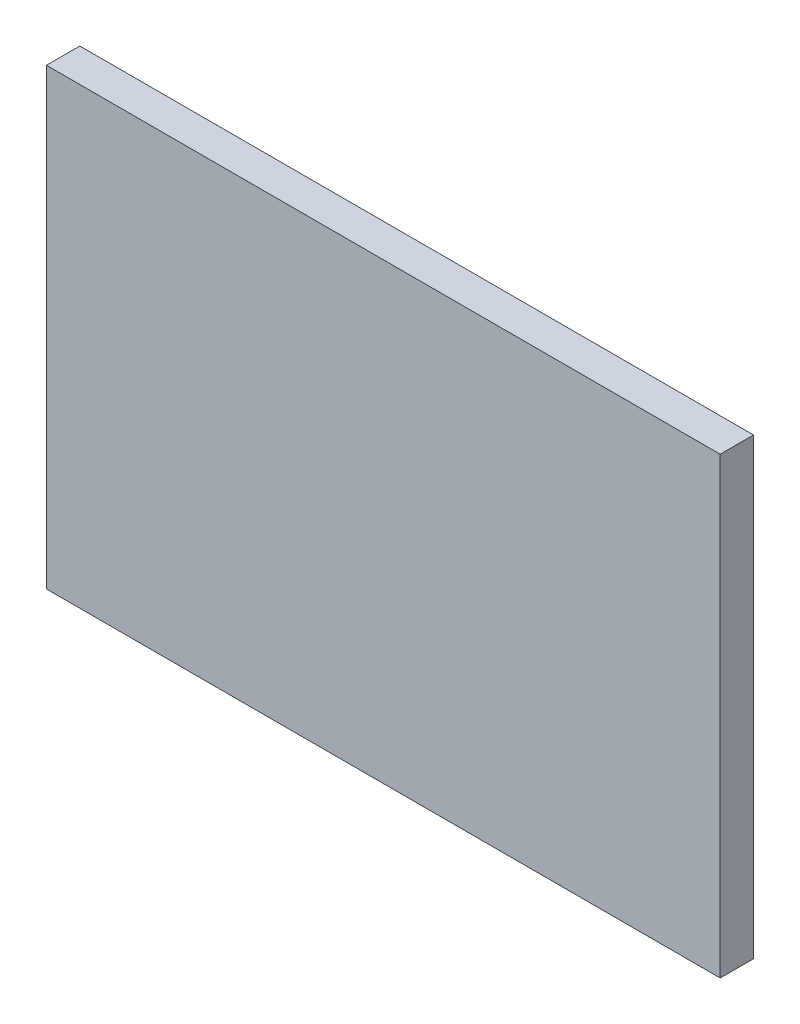
SolidWorks part; units mm, degrees
ref_plane "前视基准面" through (0, 0, 0) normal (0, 0, 1) x (1, 0, 0)
ref_plane "上视基准面" through (0, 0, 0) normal (0, 1, 0) x (1, 0, 0)
ref_plane "右视基准面" through (0, 0, 0) normal (1, 0, 0) x (0, 0, -1)
other "Configuration Table"
sketch "草图1" plane through (0, 0, 0) normal (0, 0, 1) x (1, 0, 0)
  line L1 (-50.5, 34) -> (50.5, 34)
  line L2 (-50.5, 34) -> (-50.5, -34)
  line L3 (-50.5, -34) -> (50.5, -34)
  line L4 (50.5, 34) -> (50.5, -34)
  line L5 (0, -34) -> (0, 34) construction
  line L6 (-50.5, 0) -> (50.5, 0) construction
  point P0 (0, 0)
  dimension "D1" = 101
  dimension "D2" = 68
extrude "凸台-拉伸1" add sketch "草图1" along normal blind 5
